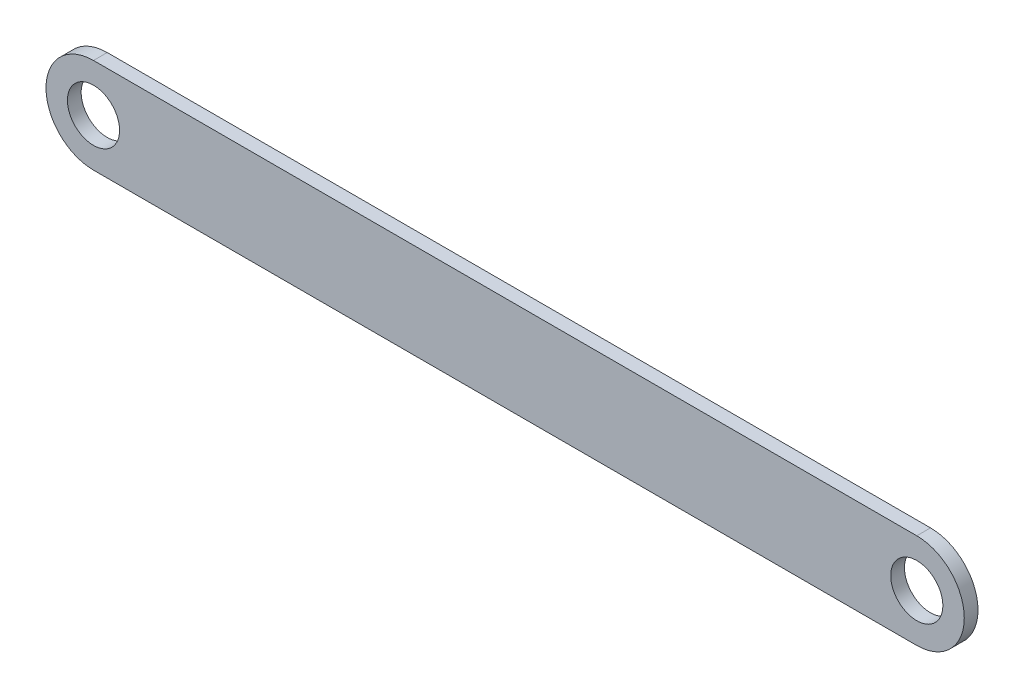
SolidWorks part; units mm, degrees
ref_plane "Alzado" through (0, 0, 0) normal (0, 0, 1) x (1, 0, 0)
ref_plane "Planta" through (0, 0, 0) normal (0, 1, 0) x (1, 0, 0)
ref_plane "Vista lateral" through (0, 0, 0) normal (1, 0, 0) x (0, 0, -1)
sketch "Croquis2" plane through (0, 0, 0) normal (0, 0, 1) x (1, 0, 0)
  line L0 (-75, 0) -> (75, 0) construction
  line L1 (-75, 8.6538) -> (75, 8.6538)
  line L2 (-75, -8.6538) -> (75, -8.6538)
  arc A0 (-75, 8.6538) -> (-75, -8.6538) centre (-75, 0) ccw
  arc A1 (75, -8.6538) -> (75, 8.6538) centre (75, 0) ccw
  point P2 (0, 0)
  dimension "D1" = 150
extrude "Saliente-Extruir1" add sketch "Croquis2" along normal blind 2.5
sketch "Croquis3" plane through (0, 0, 2.5) normal (0, 0, 1) x (1, 0, 0)
  circle A0 centre (-75, 0) radius 4.75
  circle A1 centre (75, 0) radius 4.75
  dimension "D1" = 9.5
extrude "Cortar-Extruir1" cut sketch "Croquis3" against normal through all
